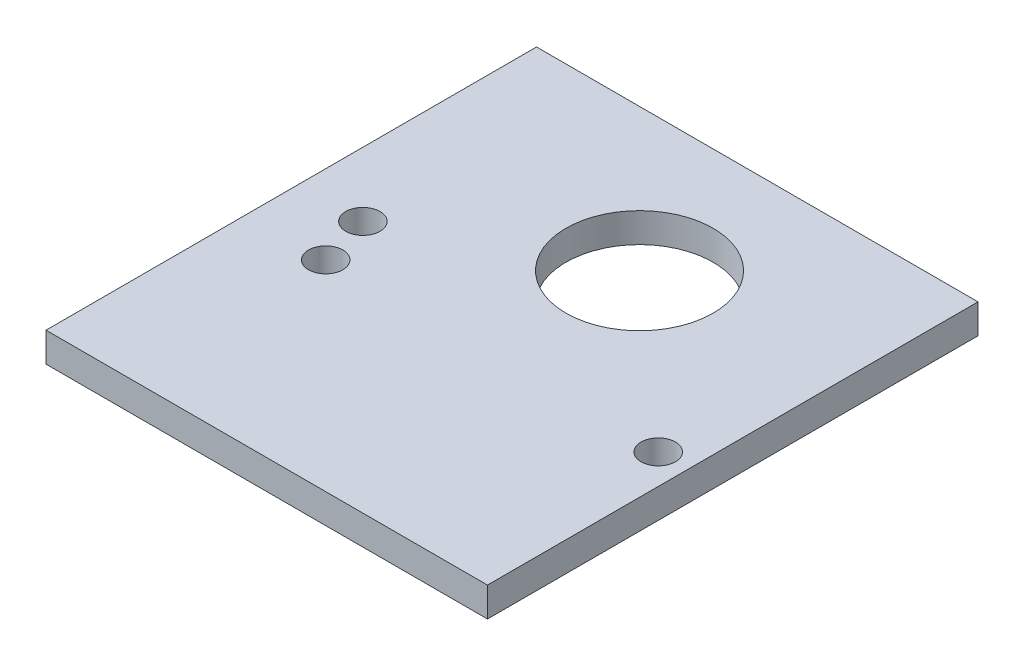
SolidWorks part; units mm, degrees
material "Acrylic (Medium-high impact)"
ref_plane "Front Plane" through (0, 0, 0) normal (0, 0, 1) x (1, 0, 0)
ref_plane "Top Plane" through (0, 0, 0) normal (0, 1, 0) x (1, 0, 0)
ref_plane "Right Plane" through (0, 0, 0) normal (1, 0, 0) x (0, 0, -1)
sketch "Sketch1" plane through (0, 0, 0) normal (0, 1, 0) x (1, 0, 0)
  line L0 (0, 0) -> (-18.45, 0) construction
  line L1 (8.75, -17.9287) -> (8.75, -10.9287) construction
  line L2 (-8.75, -17.9287) -> (-8.75, -10.9287) construction
  line L3 (-8.75, -17.9287) -> (8.75, -17.9287) construction
  line L4 (0, 0) -> (18.45, 0) construction
  line L5 (18.45, -1.75) -> (18.45, -7.0415) construction
  line L6 (18.45, -7.0415) -> (16.95, -7.0415) construction
  line L7 (-18.45, -1.75) -> (-18.45, -7.0415) construction
  line L8 (-18.45, -7.0415) -> (-16.95, -7.0415) construction
  arc A0 (8.75, -10.9287) -> (-8.75, -10.9287) centre (0, 0) ccw construction
  circle A1 centre (0, 8) radius 2.5 construction
  circle A2 centre (18.45, -1.75) radius 1.75 construction
  circle A3 centre (-18.45, -1.75) radius 1.75
  circle A4 centre (16.95, -7.0415) radius 1.75
  circle A5 centre (-16.95, -7.0415) radius 1.75
  dimension "D1" = 28
  dimension "D2" = 5
  dimension "D6" = 3.5
  dimension "D7" = 40.4
  dimension "D8" = 1.5
  dimension "D9" = 2
  dimension "D10" = 2
  dimension "D3" = 8
  dimension "D4" = 7
  dimension "D5" = 17.5
sketch "Sketch2" plane through (0, 0, 0) normal (0, 1, 0) x (1, 0, 0)
  line L0 (0, 0) -> (-25, 0) construction
  line L1 (-25, 22.5) -> (20, 22.5)
  line L2 (-25, 22.5) -> (-25, -27.5)
  line L3 (-25, -27.5) -> (20, -27.5)
  line L4 (20, 22.5) -> (20, -27.5)
  line L5 (0, 0) -> (20, 0) construction
  line L6 (0, 0) -> (0, 17.5) construction
  line L7 (0, 0) -> (0, -22.5) construction
  circle A0 centre (0, 8) radius 2.5 construction
  circle A1 centre (0, 8) radius 7.5
  dimension "D5" = 5
  dimension "D10" = 15
  dimension "D1" = 45
  dimension "D2" = 50
  dimension "D3" = 17.5
  dimension "D4" = 8
  dimension "D6" = 9.5
  dimension "D7" = 25
  dimension "D8" = 20
  dimension "D9" = 22.5
extrude "Boss-Extrude1" add sketch "Sketch2" against normal blind 3
extrude "Cut-Extrude1" cut sketch "Sketch1" against normal up to surface (3 mm away) up to face at (0, -3, -0.5)
